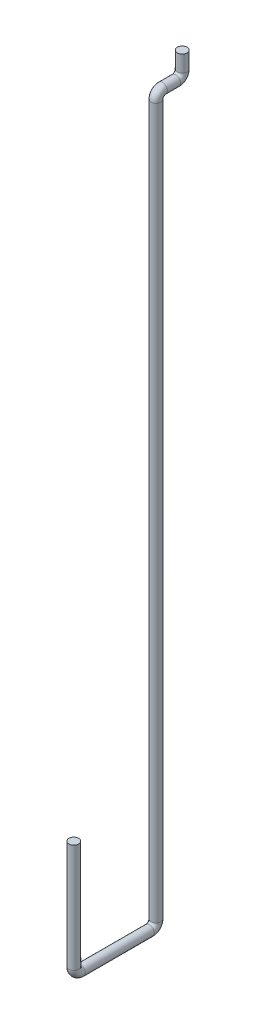
SolidWorks part; units mm, degrees
material "Сталь 3 ГОСТ 535-88"
ref_plane "Спереди" through (0, 0, 0) normal (0, 0, 1) x (1, 0, 0)
ref_plane "Сверху" through (0, 0, 0) normal (0, 1, 0) x (1, 0, 0)
ref_plane "Справа" through (0, 0, 0) normal (1, 0, 0) x (0, 0, -1)
sketch "Эскиз1" plane through (0, 0, 0) normal (1, 0, 0) x (0, 0, -1)
  line L0 (0, 0) -> (0, -5)
  line L1 (-2, -7) -> (-6, -7)
  line L2 (-8, -9) -> (-8, -225)
  line L3 (-10, -227) -> (-31, -227)
  line L4 (-33, -225) -> (-33, -192)
  arc A0 (-31, -227) -> (-33, -225) centre (-31, -225) cw
  arc A1 (-8, -225) -> (-10, -227) centre (-10, -225) cw
  arc A2 (-8, -9) -> (-6, -7) centre (-6, -9) cw
  arc A3 (0, -5) -> (-2, -7) centre (-2, -5) cw
  point P3 (-8, -192)
  point P10 (-33, -227)
  point P13 (-8, -227)
  point P16 (-8, -7)
  point P19 (0, -7)
  point P20 (-8, -49)
  dimension "D7" = 2
  dimension "D3" = 2
  dimension "D1" = 7
  dimension "D2" = 8
  dimension "D4" = 25
  dimension "D5" = 35
  dimension "D6" = 90
  dimension "D8" = 220
  dimension "D10" = 40
sketch "Эскиз3" plane through (0, 0, 0) normal (0, 1, 0) x (1, 0, 0)
  circle A0 centre (0, 0) radius 1.5
  dimension "D1" = 3
sweep "По траектории1" add profiles "Эскиз3" path "Эскиз1"
